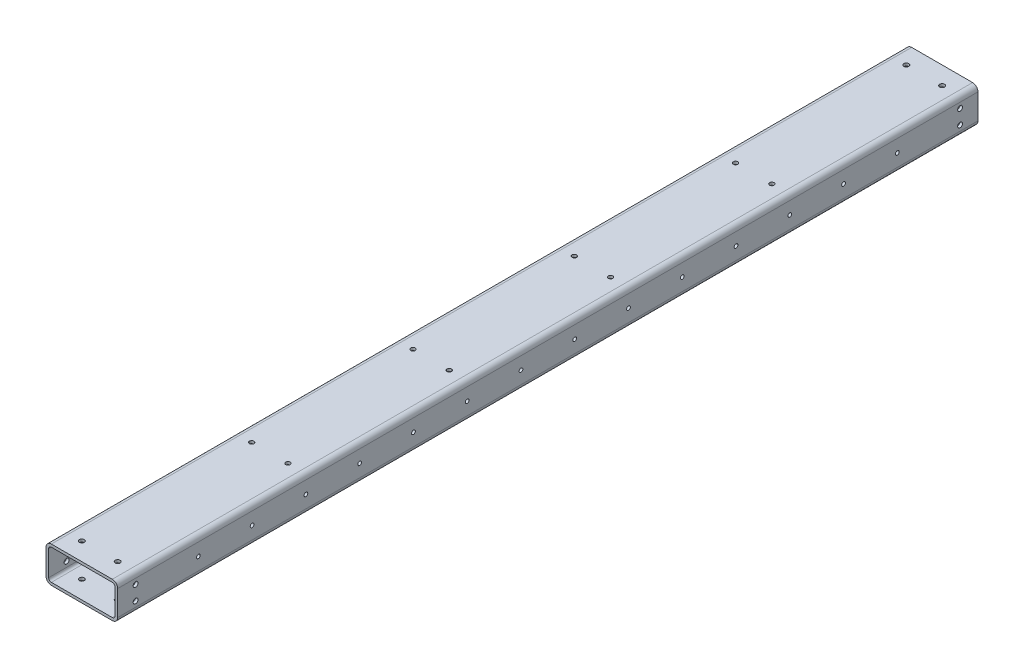
SolidWorks part; units mm, degrees
material "1.0038 (S235JRG2)"
ref_plane "Ebene vorne" through (0, 0, 0) normal (0, 0, 1) x (1, 0, 0)
ref_plane "Ebene oben" through (0, 0, 0) normal (0, 1, 0) x (1, 0, 0)
ref_plane "Ebene rechts" through (0, 0, 0) normal (1, 0, 0) x (0, 0, -1)
sketch "Skizze1" plane through (0, 0, 0) normal (0, 0, 1) x (1, 0, 0)
  line L0 (0, 0) -> (0, 67.8952) construction
  line L1 (-34, 20) -> (34, 20)
  line L2 (0, 0) -> (65.406, 0) construction
  line L3 (40, 14) -> (40, -14)
  line L4 (-40, 14) -> (-40, -14)
  line L5 (-34, -20) -> (34, -20)
  line L6 (-37, 14) -> (-37, -14)
  line L7 (-34, -17) -> (34, -17)
  line L8 (37, 14) -> (37, -14)
  line L9 (-34, 17) -> (34, 17)
  arc A0 (34, 20) -> (40, 14) centre (34, 14) cw
  arc A1 (-34, 20) -> (-40, 14) centre (-34, 14) ccw
  arc A2 (-34, -20) -> (-40, -14) centre (-34, -14) cw
  arc A3 (34, -20) -> (40, -14) centre (34, -14) ccw
  arc A4 (-34, -17) -> (-37, -14) centre (-34, -14) cw
  arc A5 (34, -17) -> (37, -14) centre (34, -14) ccw
  arc A6 (34, 17) -> (37, 14) centre (34, 14) cw
  arc A7 (-34, 17) -> (-37, 14) centre (-34, 14) ccw
  point P12 (40, 0)
  point P13 (0, 20)
  point P19 (-40, 0)
  dimension "D1" = 6
  dimension "D3" = 80
  dimension "D4" = 40
  dimension "D2" = 3
extrude "Aufsatz-Linear austragen1" add sketch "Skizze1" along normal mid plane 960
hole_wizard "M5 Gewindebohrung1" positions "Skizze3" profile "Skizze4" tap size "M5" standard "DIN"
sketch "Skizze3" plane through (40, 0, 0) normal (1, 0, 0) x (0, 0, -1)
  line L0 (480, -14) -> (480, 14) construction
  line L1 (-480, 20) -> (480, 20) construction
  point P0 (390, 0)
  dimension "D1" = 90
  dimension "D2" = 20
sketch "Skizze4" plane through (40, 0, -390) normal (0, 1, 0) x (0, 0, -1)
  line L0 (0, 0) -> (0, 15.2618)
  line L1 (0, 15.2618) -> (2.1, 14)
  line L2 (2.1, 14) -> (2.1, 0)
  line L5 (2.1, 0) -> (0, 0)
  line L10 (0, 15.2618) -> (-2.1, 14) construction
  line L11 (0, -6.35) -> (0, 107.95) construction
  dimension "Bohrerdurchmesser" = 4.2
  dimension "Bohrungstiefe" = 14
  dimension "Spitzenwinkel" = 118
pattern_linear "Lineares Muster1" count 14 spacing 60 along (0, 0, 1) of "M5 Gewindebohrung1"
sketch "Skizze5" plane through (40, 0, 0) normal (1, 0, 0) x (0, 0, -1)
  line L0 (0, 0) -> (0, 129.5758) construction
  line L1 (460, 8) -> (460, -8) construction
  line L2 (-480, 20) -> (480, 20) construction
  line L3 (-480, -20) -> (480, -20) construction
  line L4 (480, -14) -> (480, 14) construction
  circle A0 centre (460, 8) radius 2.75
  circle A1 centre (460, -8) radius 2.75
  circle A2 centre (-460, -8) radius 2.75
  circle A3 centre (-460, 8) radius 2.75
  dimension "D3" = 5.5
  dimension "D1" = 12
  dimension "D2" = 12
  dimension "D4" = 20
extrude "Schnitt-Linear austragen1" cut sketch "Skizze5" against normal blind 100
sketch "Skizze6" plane through (0, 20, 0) normal (0, 1, 0) x (1, 0, 0)
  line L0 (0, 0) -> (153.3511, 0) construction
  line L1 (0, 0) -> (0, -503.6188) construction
  line L2 (40, -480) -> (40, 480) construction
  line L3 (34, -480) -> (-34, -480) construction
  line L4 (-40, -480) -> (-40, 480) construction
  circle A0 centre (20, -460) radius 2.75
  circle A1 centre (-20, -460) radius 2.75
  circle A2 centre (20, 460) radius 2.75
  circle A3 centre (-20, 460) radius 2.75
  dimension "D3" = 5.5
  dimension "D5" = 20
  dimension "D1" = 20
  dimension "D2" = 20
  dimension "D4" = 20
extrude "Schnitt-Linear austragen2" cut sketch "Skizze6" against normal blind 100
sketch "Skizze7" plane through (-40, 0, 0) normal (-1, 0, 0) x (0, 0, 1)
  circle A13 centre (270, 0) radius 2.1 construction
  circle A14 centre (90, 0) radius 2.1 construction
  circle A15 centre (-90, 0) radius 2.1 construction
  circle A16 centre (-270, 0) radius 2.1 construction
  circle A17 centre (270, 0) radius 2.1
  circle A18 centre (90, 0) radius 2.1
  circle A19 centre (-90, 0) radius 2.1
  circle A20 centre (-270, 0) radius 2.1
extrude "Schnitt-Linear austragen3" cut sketch "Skizze7" against normal blind 10
sketch "Skizze8" plane through (0, 20, 0) normal (0, 1, 0) x (1, 0, 0)
  line L0 (0, 0) -> (0, 503.6188) construction
  line L1 (0, 0) -> (205.6298, 0) construction
  line L2 (34, 480) -> (-34, 480) construction
  line L3 (40, -480) -> (40, 480) construction
  line L4 (20, 90) -> (20, 270) construction
  line L5 (20, 270) -> (-20.5, 270) construction
  line L6 (-40, -480) -> (-40, 480) construction
  line L7 (-20.5, 270) -> (-20.5, 90) construction
  line L8 (-20.5, 90) -> (20, 90) construction
  circle A0 centre (20, 270) radius 2.5
  circle A1 centre (20, 90) radius 2.5
  circle A2 centre (-20.5, 90) radius 2.5
  circle A3 centre (-20.5, 270) radius 2.5
  circle A4 centre (20, -90) radius 2.5
  circle A5 centre (-20.5, -90) radius 2.5
  circle A6 centre (20, -270) radius 2.5
  circle A7 centre (-20.5, -270) radius 2.5
  dimension "D1" = 5
  dimension "D2" = 210
  dimension "D3" = 180
  dimension "D4" = 20
  dimension "D5" = 19.5
extrude "Schnitt-Linear austragen4" cut sketch "Skizze8" against normal blind 100
sketch "Skizze10" plane through (0, -20, 0) normal (0, -1, 0) x (1, 0, 0)
  line L0 (-9, -409) -> (-9, -394) construction
  line L1 (-9, -394) -> (-9, 348) construction
  line L3 (-34, -480) -> (34, -480) construction
  line L4 (40, 480) -> (40, -480) construction
  circle A0 centre (-9, -409) radius 2.75
  circle A1 centre (-9, 348) radius 2.75
  circle A2 centre (-9, -394) radius 2.75
  dimension "D2" = 5.5
  dimension "D4" = 71
  dimension "D1" = 49
  dimension "D3" = 15
  dimension "D5" = 742
extrude "Schnitt-Linear austragen6" cut sketch "Skizze10" against normal blind 10
